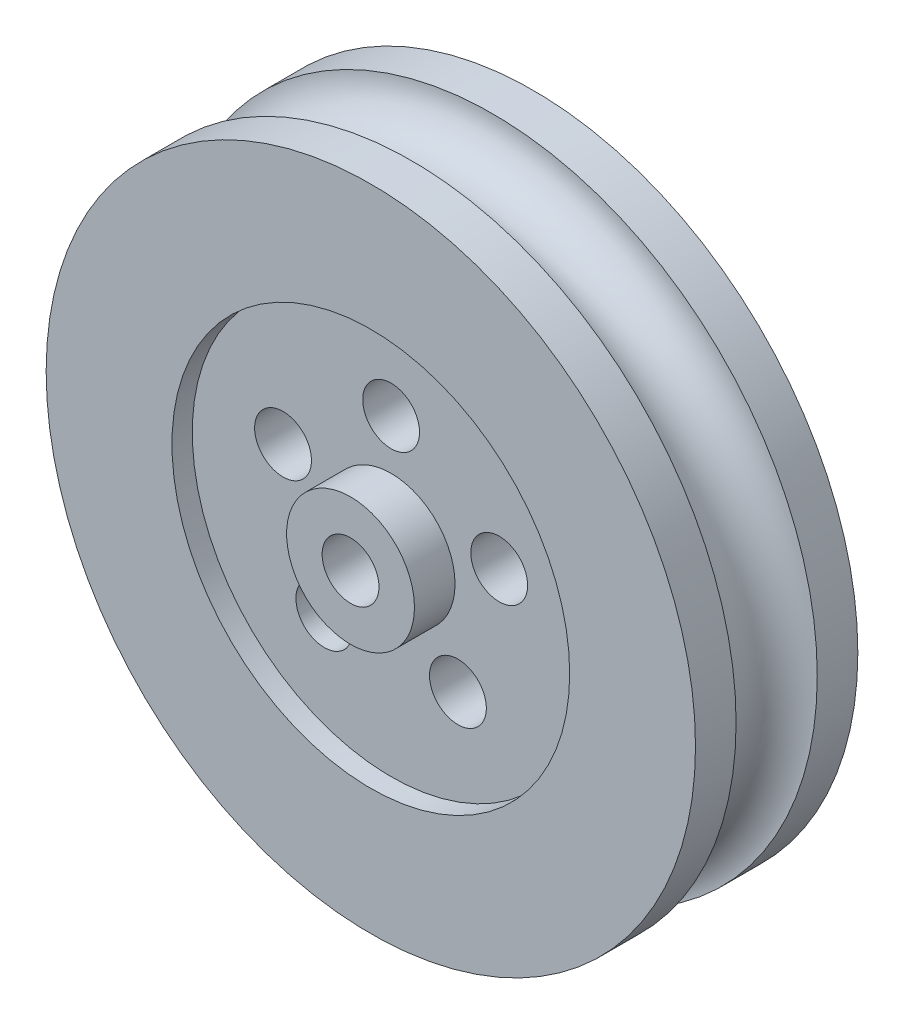
SolidWorks part; units mm, degrees
ref_plane "Front Plane" through (0, 0, 0) normal (0, 0, 1) x (1, 0, 0)
ref_plane "Top Plane" through (0, 0, 0) normal (0, 1, 0) x (1, 0, 0)
ref_plane "Right Plane" through (0, 0, 0) normal (1, 0, 0) x (0, 0, -1)
sketch "Sketch2" plane through (0, 0, 0) normal (0, 0, 1) x (1, 0, 0)
  circle A0 centre (0, 0) radius 16
  circle A1 centre (0, 0) radius 1.4
  dimension "D1" = 32
  dimension "D2" = 2.8
extrude "Boss-Extrude1" add sketch "Sketch2" along normal mid plane 8
sketch "Sketch3" plane through (0, 0, 4) normal (0, 0, 1) x (1, 0, 0)
  circle A0 centre (0, 0) radius 9.8
  dimension "D1" = 19.6
extrude "Cut-Extrude1" cut sketch "Sketch3" against normal blind 1
sketch "Sketch6" plane through (0, 0, 3) normal (0, 0, 1) x (1, 0, 0)
  circle A0 centre (0, 0) radius 3.15
  circle A1 centre (0, 0) radius 1.4 construction
  circle A2 centre (0, 0) radius 1.4
  dimension "D1" = 6.3
extrude "Boss-Extrude2" add sketch "Sketch6" along normal blind 2
mirror "Mirror1" about plane through (0, 0, 0) normal (0, 0, 1) of "Boss-Extrude2", "Cut-Extrude1"
sketch "Sketch4" plane through (0, 0, 3) normal (0, 0, 1) x (1, 0, 0)
  circle A0 centre (0, 5.6) radius 1.4
  dimension "D1" = 2.8
  dimension "D2" = 5.6
extrude "Cut-Extrude2" cut sketch "Sketch4" against normal through all
pattern_circular "CirPattern1" count 5 over 360 about axis through (0, 0, 0) along (0, 0, 1) of "Cut-Extrude2"
sketch "Sketch5" plane through (0, 0, 0) normal (0, 1, 0) x (1, 0, 0)
  line L0 (0, 19.2675) -> (0, -19.2675) construction
  line L8 (16, -4) -> (16, 4) construction
  circle A0 centre (16, 0) radius 2
  point P4 (0, 0)
  dimension "D1" = 4
revolve "Cut-Revolve1" cut sketch "Sketch5" angle 360 about L0
